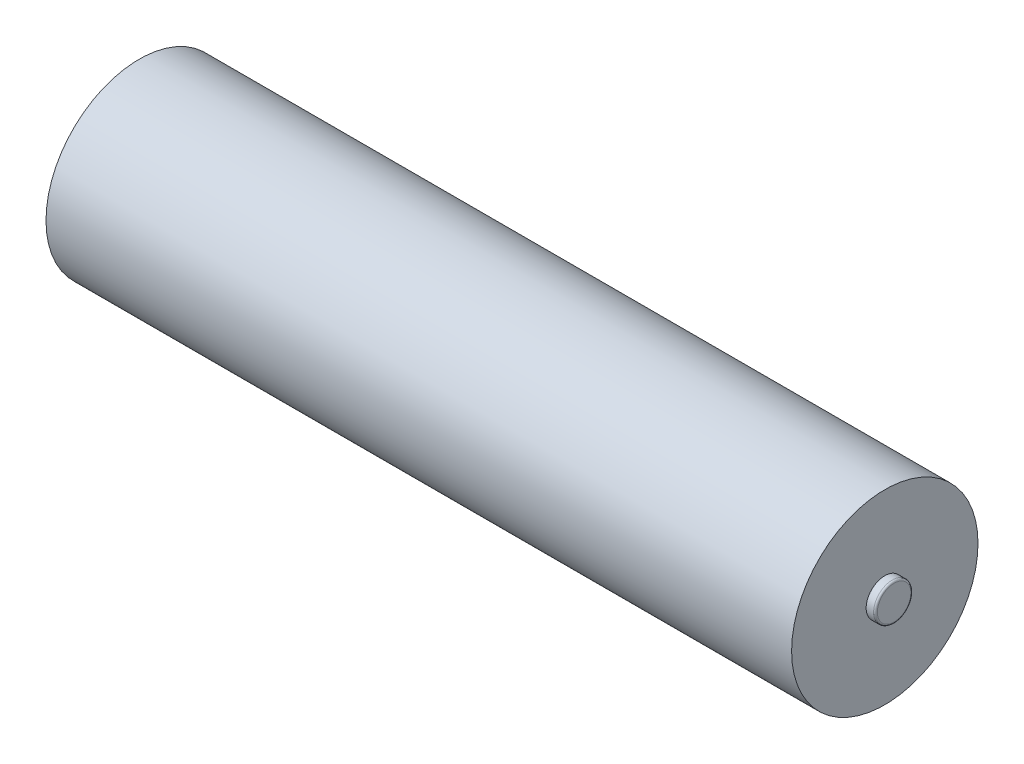
SolidWorks part; units mm, degrees
ref_plane "Front Plane" through (0, 0, 0) normal (0, 0, 1) x (1, 0, 0)
ref_plane "Top Plane" through (0, 0, 0) normal (0, 1, 0) x (1, 0, 0)
ref_plane "Right Plane" through (0, 0, 0) normal (1, 0, 0) x (0, 0, -1)
sketch "Sketch1" plane through (0, 0, 0) normal (1, 0, 0) x (0, 0, -1)
  circle A0 centre (0, 0) radius 50
  dimension "D1" = 100
extrude "Boss-Extrude1" add sketch "Sketch1" along normal mid plane 400
sketch "Sketch2" plane through (200, 0, 0) normal (1, 0, 0) x (0, 0, -1)
  circle A0 centre (0, 0) radius 10
  dimension "D1" = 20
extrude "Boss-Extrude2" add sketch "Sketch2" along normal blind 5
fillet "Fillet1" radius 1 1 edges at (205, 0, -10)
mirror "Mirror3" about plane through (0, 0, 0) normal (1, 0, 0) of "Fillet1", "Boss-Extrude2"
